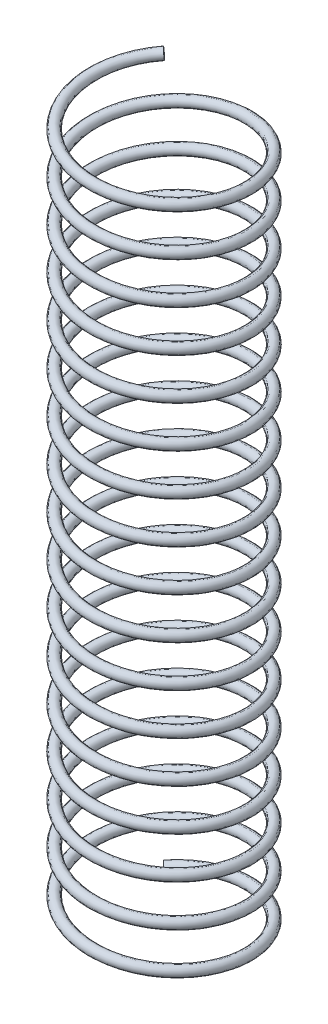
SolidWorks part; units mm, degrees
material "可锻铸铁"
ref_plane "前视基准面" through (0, 0, 0) normal (0, 0, 1) x (1, 0, 0)
ref_plane "上视基准面" through (0, 0, 0) normal (0, 1, 0) x (1, 0, 0)
ref_plane "右视基准面" through (0, 0, 0) normal (1, 0, 0) x (0, 0, -1)
sketch "草图1" plane through (0, 0, 0) normal (0, 1, 0) x (1, 0, 0)
  circle A0 centre (0, 0) radius 7.5
  dimension "D1" = 15
curve "螺旋线/涡状线1" pitch 4 height 68 turns 17
ref_plane "基准面1" through (-5.3033, 0, -5.3033) normal (0.7046, 0.0846, -0.7046) x (-0.694, 0.2892, -0.6593)
sketch "草图2" plane through (-5.3033, 0, -5.3033) normal (0.7046, 0.0846, -0.7046) x (-0.694, 0.2892, -0.6593)
  circle A0 centre (0, 0) radius 0.5
  dimension "D1" = 1
sweep "扫描1" add profiles "草图2" path "螺旋线/涡状线1"
